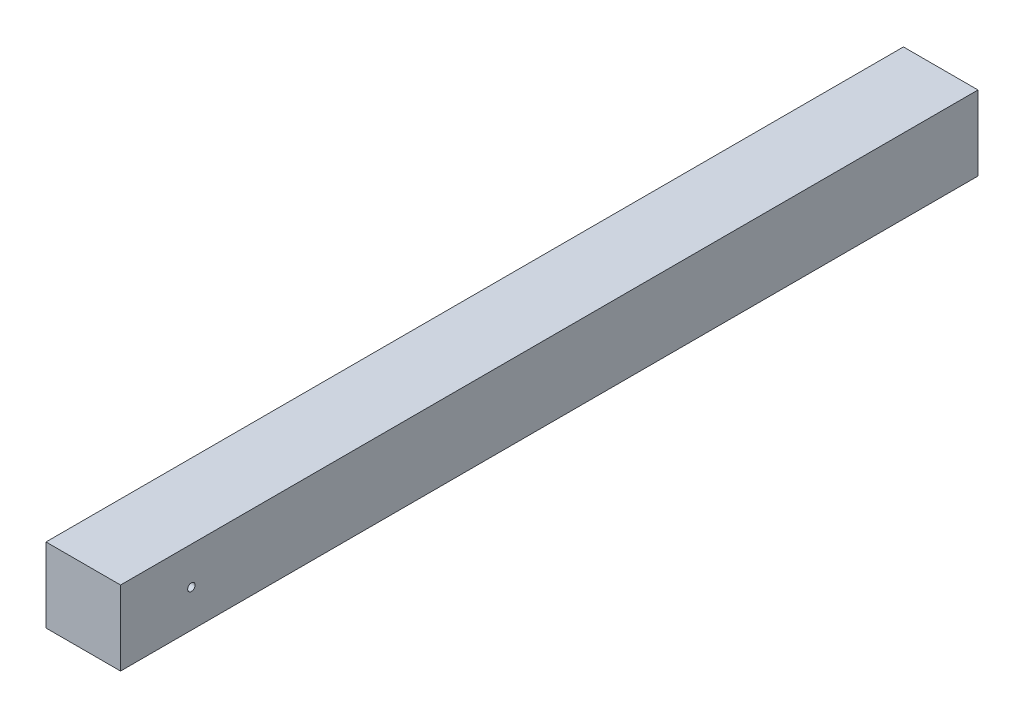
SolidWorks part; units mm, degrees
material "Pine"
ref_plane "Front Plane" through (0, 0, 0) normal (0, 0, 1) x (1, 0, 0)
ref_plane "Top Plane" through (0, 0, 0) normal (0, 1, 0) x (1, 0, 0)
ref_plane "Right Plane" through (0, 0, 0) normal (1, 0, 0) x (0, 0, -1)
sketch "Sketch1" plane through (0, 0, 0) normal (0, 0, 1) x (1, 0, 0)
  line L1 (-50, 50) -> (50, 50)
  line L2 (-50, 50) -> (-50, -50)
  line L3 (-50, -50) -> (50, -50)
  line L4 (50, 50) -> (50, -50)
  line L5 (-50, 50) -> (50, -50) construction
  line L6 (-50, -50) -> (50, 50) construction
  point P0 (0, 0)
  dimension "D1" = 100
extrude "Boss-Extrude1" add sketch "Sketch1" along normal mid plane 1150
sketch "Sketch2" plane through (50, 0, 0) normal (1, 0, 0) x (0, 0, -1)
  circle A0 centre (-480, 0) radius 5
  dimension "D1" = 10
  dimension "D2" = 480
extrude "Cut-Extrude1" cut sketch "Sketch2" against normal through all
